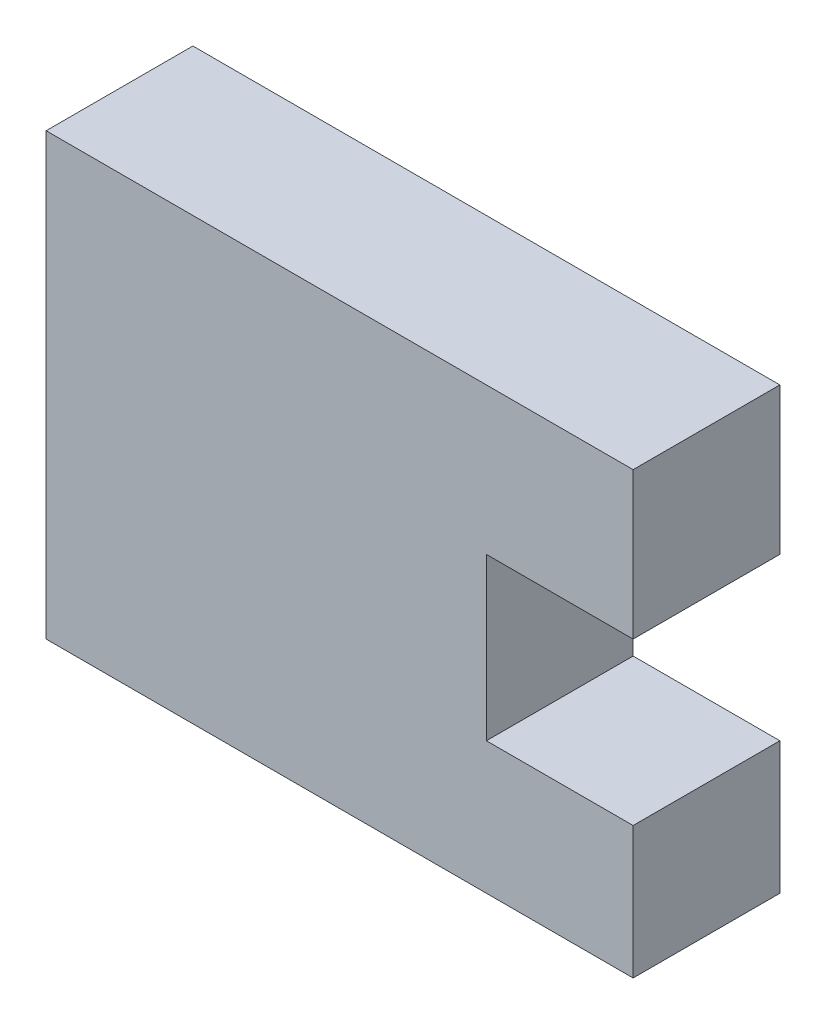
SolidWorks part; units mm, degrees
ref_plane "Front Plane" through (0, 0, 0) normal (0, 0, 1) x (1, 0, 0)
ref_plane "Top Plane" through (0, 0, 0) normal (0, 1, 0) x (1, 0, 0)
ref_plane "Right Plane" through (0, 0, 0) normal (1, 0, 0) x (0, 0, -1)
sketch "Sketch1" plane through (0, 0, 0) normal (0, 0, 1) x (1, 0, 0)
  line L0 (80, 40) -> (60, 40)
  line L1 (0, 0) -> (80, 0)
  line L2 (0, 0) -> (0, 60)
  line L3 (0, 60) -> (80, 60)
  line L4 (80, 0) -> (80, 18)
  line L5 (60, 40) -> (60, 18)
  line L6 (60, 18) -> (80, 18)
  line L7 (80, 40) -> (80, 60)
  dimension "D1" = 80
  dimension "D2" = 60
  dimension "D3" = 20
  dimension "D4" = 22
  dimension "D5" = 20
extrude "Boss-Extrude1" add sketch "Sketch1" along normal blind 20
